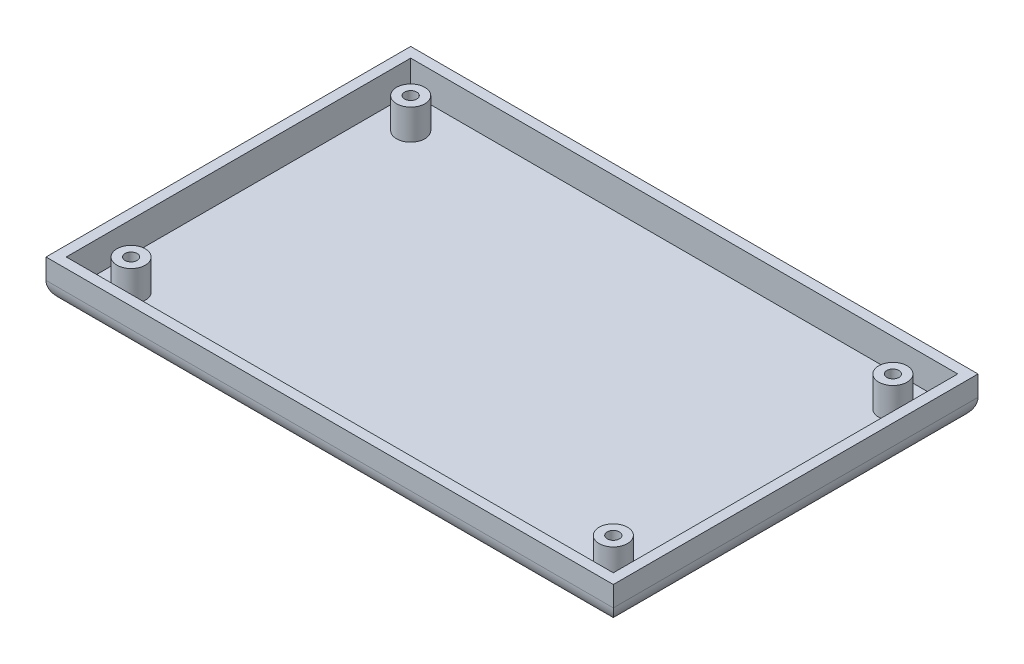
SolidWorks part; units mm, degrees
ref_plane "Front Plane" through (0, 0, 0) normal (0, 0, 1) x (1, 0, 0)
ref_plane "Top Plane" through (0, 0, 0) normal (0, 1, 0) x (1, 0, 0)
ref_plane "Right Plane" through (0, 0, 0) normal (1, 0, 0) x (0, 0, -1)
sketch "Sketch1" plane through (0, 0, 0) normal (0, 1, 0) x (1, 0, 0)
  line L1 (0, 0) -> (140, 0)
  line L2 (0, 0) -> (0, 90)
  line L3 (0, 90) -> (140, 90)
  line L4 (140, 0) -> (140, 90)
  dimension "D1" = 140
  dimension "D2" = 90
extrude "Boss-Extrude2" add sketch "Sketch1" along normal blind 10
sketch "Sketch2" plane through (0, 10, 0) normal (0, 1, 0) x (1, 0, 0)
  line L0 (0, 0) -> (140, 90) construction
  line L1 (0, 90) -> (140, 0) construction
  line L2 (0, 90) -> (0, 0) construction
  line L3 (2.5, 87.5) -> (137.5, 87.5)
  line L4 (2.5, 87.5) -> (2.5, 2.5)
  line L5 (2.5, 2.5) -> (137.5, 2.5)
  line L6 (137.5, 87.5) -> (137.5, 2.5)
  line L7 (2.5, 87.5) -> (137.5, 2.5) construction
  line L8 (2.5, 2.5) -> (137.5, 87.5) construction
  line L9 (140, 90) -> (0, 90) construction
  point P8 (70, 45)
  dimension "D1" = 2.5
  dimension "D2" = 2.5
extrude "Cut-Extrude1" cut sketch "Sketch2" against normal blind 7.5
sketch "Sketch4" plane through (0, 2.5, 0) normal (0, 1, 0) x (1, 0, 0)
  line L0 (137.5, 87.5) -> (2.5, 87.5) construction
  line L1 (2.5, 87.5) -> (2.5, 2.5) construction
  line L2 (2.5, 2.5) -> (137.5, 2.5) construction
  line L4 (137.5, 2.5) -> (137.5, 87.5) construction
  circle A0 centre (10.5, 79.5) radius 3.5
  circle A1 centre (10.5, 10.5) radius 3.5
  circle A2 centre (129.5, 10.5) radius 3.5
  circle A3 centre (129.5, 79.5) radius 3.5
  dimension "D3" = 7
  dimension "D6" = 7
  dimension "D8" = 7
  dimension "D9" = 7
  dimension "D1" = 8
  dimension "D2" = 8
  dimension "D4" = 8
  dimension "D5" = 8
  dimension "D7" = 8
extrude "Boss-Extrude3" add sketch "Sketch4" along normal blind 7.5
sketch "Sketch5" plane through (0, 10, 0) normal (0, 1, 0) x (1, 0, 0)
  circle A0 centre (10.5, 10.5) radius 1.5
  circle A1 centre (10.5, 79.5) radius 1.5
  circle A2 centre (129.5, 79.5) radius 1.5
  circle A3 centre (129.5, 10.5) radius 1.5
  dimension "D1" = 3
  dimension "D2" = 3
  dimension "D3" = 3
  dimension "D4" = 3
extrude "Cut-Extrude2" cut sketch "Sketch5" against normal through all
fillet "Fillet1" radius 5 4 edges at (140, 0, -45) (70, 0, 0) (0, 0, -45) (70, 0, -90)
